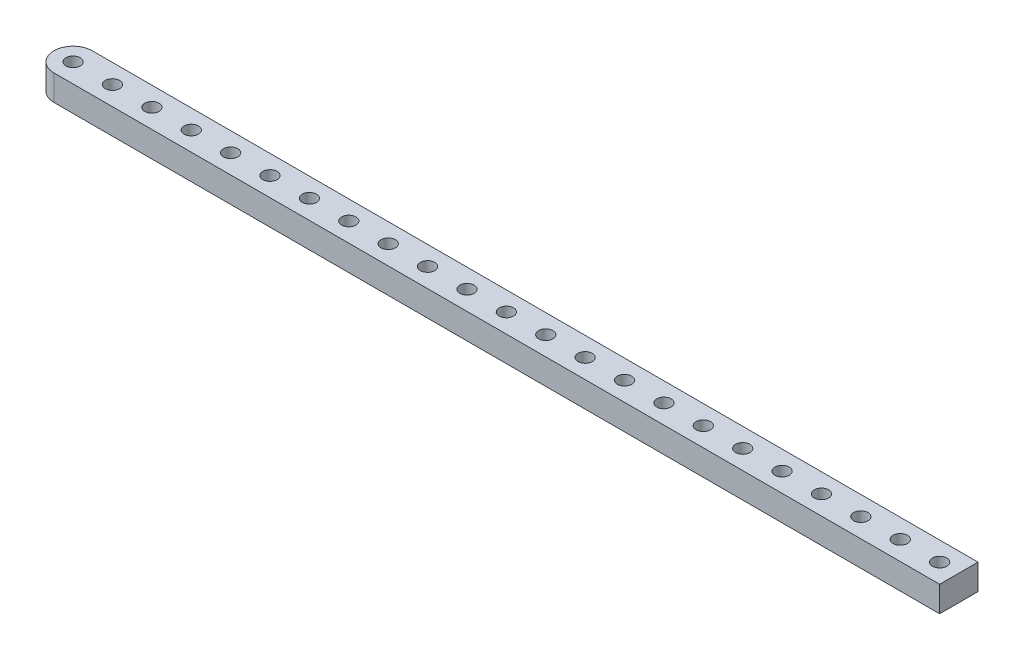
SolidWorks part; units mm, degrees
ref_plane "Front Plane" through (0, 0, 0) normal (0, 0, 1) x (1, 0, 0)
ref_plane "Top Plane" through (0, 0, 0) normal (0, 1, 0) x (1, 0, 0)
ref_plane "Right Plane" through (0, 0, 0) normal (1, 0, 0) x (0, 0, -1)
ref_plane "Plane1" through (0, 6.35, 0) normal (0, 1, 0) x (1, 0, 0)
sketch "Sketch1" plane through (0, 6.35, 0) normal (0, 1, 0) x (1, 0, 0)
  line L0 (156.464, 4.7625) -> (-156.464, 4.7625)
  line L1 (-156.464, -4.7625) -> (156.464, -4.7625)
  arc A0 (156.464, -4.7625) -> (156.464, 4.7625) centre (156.464, 0) ccw
  arc A1 (-156.464, 4.7625) -> (-156.464, -4.7625) centre (-156.464, 0) ccw
  circle A2 centre (156.464, 0) radius 1.778
  circle A3 centre (146.685, 0) radius 1.778
  circle A4 centre (136.906, 0) radius 1.778
  circle A5 centre (127.127, 0) radius 1.778
  circle A6 centre (117.348, 0) radius 1.778
  circle A7 centre (107.569, 0) radius 1.778
  circle A8 centre (97.79, 0) radius 1.778
  circle A9 centre (88.011, 0) radius 1.778
  circle A10 centre (78.232, 0) radius 1.778
  circle A11 centre (68.453, 0) radius 1.778
  circle A12 centre (58.674, 0) radius 1.778
  circle A13 centre (48.895, 0) radius 1.778
  circle A14 centre (39.116, 0) radius 1.778
  circle A15 centre (29.337, 0) radius 1.778
  circle A16 centre (19.558, 0) radius 1.778
  circle A17 centre (9.779, 0) radius 1.778
  circle A18 centre (0, 0) radius 1.778
  circle A19 centre (-9.779, 0) radius 1.778
  circle A20 centre (-19.558, 0) radius 1.778
  circle A21 centre (-29.337, 0) radius 1.778
  circle A22 centre (-39.116, 0) radius 1.778
  circle A23 centre (-48.895, 0) radius 1.778
  circle A24 centre (-58.674, 0) radius 1.778
  circle A25 centre (-68.453, 0) radius 1.778
  circle A26 centre (-78.232, 0) radius 1.778
  circle A27 centre (-88.011, 0) radius 1.778
  circle A28 centre (-97.79, 0) radius 1.778
  circle A29 centre (-107.569, 0) radius 1.778
  circle A30 centre (-117.348, 0) radius 1.778
  circle A31 centre (-127.127, 0) radius 1.778
  circle A32 centre (-136.906, 0) radius 1.778
  circle A33 centre (-146.685, 0) radius 1.778
  circle A34 centre (-156.464, 0) radius 1.778
extrude "Boss-Extrude1" add sketch "Sketch1" against normal blind 6.35
sketch "Sketch2" plane through (0, 6.35, 0) normal (0, 1, 0) x (1, 0, 0)
  line L5 (-156.464, -4.7625) -> (156.464, -4.7625) construction
  line L6 (63.4365, -4.7625) -> (163.5653, -4.7625)
  line L7 (63.4365, -4.7625) -> (63.4365, 4.7625)
  line L8 (63.4365, 4.7625) -> (163.5653, 4.7625)
  line L9 (163.5653, -4.7625) -> (163.5653, 4.7625)
  circle A1 centre (58.674, 0) radius 1.778 construction
  dimension "D1" = 4.7625
extrude "Cut-Extrude1" cut sketch "Sketch2" against normal through all
